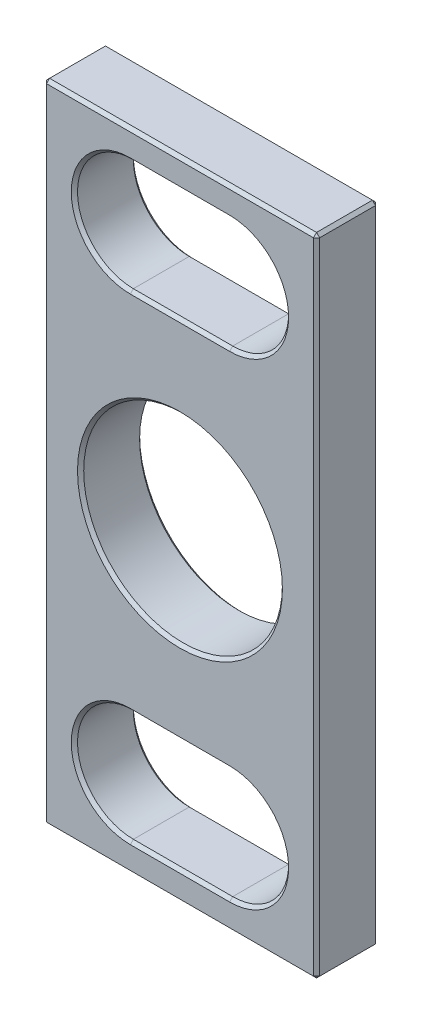
SolidWorks part; units mm, degrees
ref_plane "Plan de face" through (0, 0, 0) normal (0, 0, 1) x (1, 0, 0)
ref_plane "Plan de dessus" through (0, 0, 0) normal (0, 1, 0) x (1, 0, 0)
ref_plane "Plan de droite" through (0, 0, 0) normal (1, 0, 0) x (0, 0, -1)
sketch "Esquisse1" plane through (0, 0, 0) normal (0, 0, 1) x (1, 0, 0)
  line L1 (0, 0) -> (22, 0)
  line L2 (0, 0) -> (0, 52)
  line L3 (0, 52) -> (22, 52)
  line L4 (22, 0) -> (22, 52)
  dimension "D1" = 52
  dimension "D2" = 22
extrude "Boss.-Extru.1" add sketch "Esquisse1" along normal blind 5
sketch "Esquisse5" plane through (0, 0, 5) normal (0, 0, 1) x (1, 0, 0)
  line L0 (11, 52) -> (11, 0) construction
  line L1 (22, 52) -> (0, 52) construction
  line L2 (0, 0) -> (22, 0) construction
  circle A0 centre (11, 26) radius 8
  dimension "D1" = 16
extrude "Enlèv. mat.-Extru.2" cut sketch "Esquisse5" against normal blind 5
sketch "Esquisse6" plane through (0, 0, 5) normal (0, 0, 1) x (1, 0, 0)
  line L0 (7, 45.2) -> (15, 45.2) construction
  line L1 (7, 49.7) -> (15, 49.7)
  line L2 (7, 40.7) -> (15, 40.7)
  line L3 (22, 52) -> (0, 52) construction
  line L4 (11, 52) -> (11, 0) construction
  line L5 (0, 0) -> (22, 0) construction
  line L6 (11, 26) -> (0, 26) construction
  line L7 (0, 52) -> (0, 0) construction
  line L8 (7, 6.8) -> (15, 6.8) construction
  line L9 (7, 2.3) -> (15, 2.3)
  line L10 (7, 11.3) -> (15, 11.3)
  line L11 (22, 52) -> (0, 52) construction
  arc A0 (7, 49.7) -> (7, 40.7) centre (7, 45.2) ccw
  arc A1 (15, 40.7) -> (15, 49.7) centre (15, 45.2) ccw
  arc A2 (7, 2.3) -> (7, 11.3) centre (7, 6.8) cw
  arc A3 (15, 11.3) -> (15, 2.3) centre (15, 6.8) cw
  point P2 (11, 45.2)
  point P19 (11, 6.8)
  dimension "D1" = 9
  dimension "D2" = 6.8
  dimension "D3" = 8
extrude "Enlèv. mat.-Extru.3" cut sketch "Esquisse6" against normal through all
chamfer "Chanfrein1" distance 0.25 angle 45 30 edges at (0, 0, 2.5) (22, 0, 2.5) (22, 52, 2.5) (11, 52, 5) (22, 26, 5) (11, 0, 5) (0, 26, 5) (0, 52, 2.5) (11, 52, 0) (22, 26, 0) (11, 0, 0) (0, 26, 0) (19, 26, 0) (19, 26, 5) (11, 49.7, 0) (19.5, 45.2, 0) (11, 40.7, 0) (2.5, 45.2, 0) (11, 49.7, 5) (19.5, 45.2, 5) (11, 40.7, 5) (2.5, 45.2, 5) (11, 11.3, 0) (19.5, 6.8, 0) (11, 2.3, 0) (2.5, 6.8, 0) (11, 11.3, 5) (19.5, 6.8, 5) (11, 2.3, 5) (2.5, 6.8, 5)
